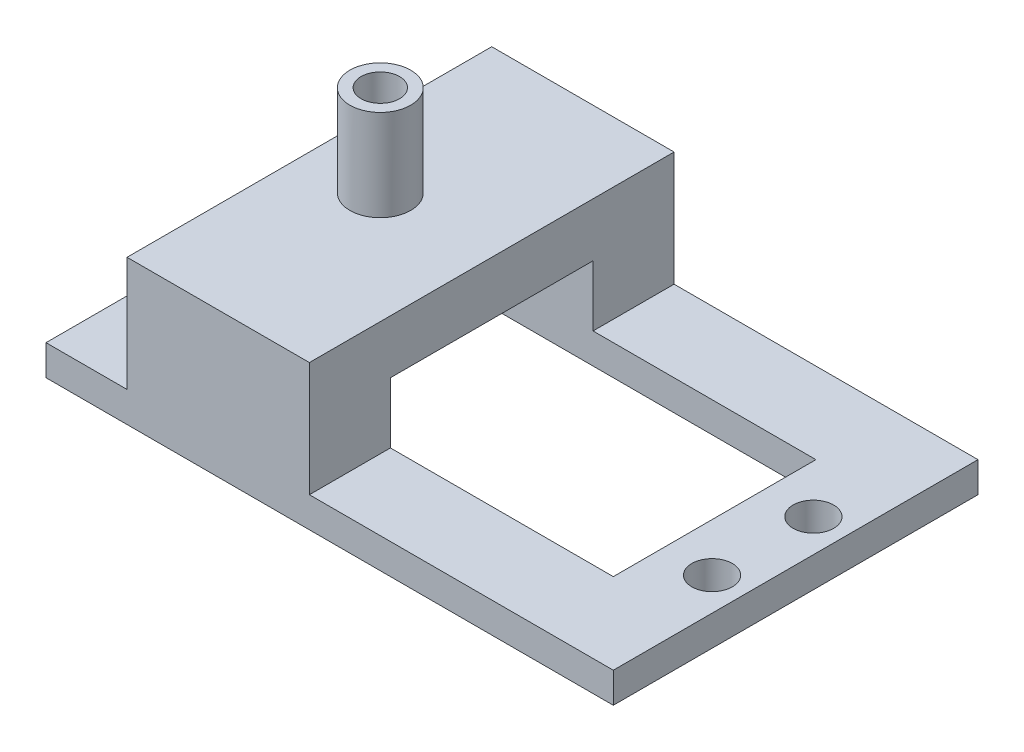
SolidWorks part; units mm, degrees
ref_plane "Front Plane" through (0, 0, 0) normal (0, 0, 1) x (1, 0, 0)
ref_plane "Top Plane" through (0, 0, 0) normal (0, 1, 0) x (1, 0, 0)
ref_plane "Right Plane" through (0, 0, 0) normal (1, 0, 0) x (0, 0, -1)
sketch "Sketch1" plane through (0, 0, 0) normal (0, 1, 0) x (1, 0, 0)
  line L1 (-29.0978, 4.5617) -> (-21.0978, 4.5617)
  line L2 (-29.0978, 4.5617) -> (-29.0978, -15.4383)
  line L3 (-29.0978, -15.4383) -> (-21.0978, -15.4383)
  line L4 (-21.0978, 4.5617) -> (-21.0978, -15.4383)
  line L5 (18.9022, 4.5617) -> (26.9022, 4.5617)
  line L6 (18.9022, 4.5617) -> (18.9022, -15.4383)
  line L7 (18.9022, -15.4383) -> (26.9022, -15.4383)
  line L8 (26.9022, 4.5617) -> (26.9022, -15.4383)
  line L9 (-29.0978, 4.5617) -> (26.9022, 4.5617)
  line L10 (-29.0978, 4.5617) -> (-29.0978, 12.5617)
  line L11 (-29.0978, 12.5617) -> (26.9022, 12.5617)
  line L12 (26.9022, 4.5617) -> (26.9022, 12.5617)
  line L13 (-29.0978, -15.4383) -> (26.9022, -15.4383)
  line L14 (-29.0978, -15.4383) -> (-29.0978, -23.4383)
  line L15 (-29.0978, -23.4383) -> (26.9022, -23.4383)
  line L16 (26.9022, -15.4383) -> (26.9022, -23.4383)
  dimension "D1" = 40
  dimension "D2" = 8
  dimension "D3" = 8
  dimension "D4" = 20
  dimension "D5" = 8
  dimension "D6" = 8
extrude "Boss-Extrude1" add sketch "Sketch1" against normal blind 3 contours L5 L12 L11 L10 L1 L9 | L4 L1 L2 L3 | L8 L5 L6 L7 | L14 L13 L16 L15
sketch "Sketch2" plane through (0, 0, 0) normal (0, 1, 0) x (1, 0, 0)
  line L0 (-29.0978, 12.5617) -> (26.9022, 12.5617) construction
  line L1 (-21.0978, 4.5617) -> (-3.0978, 4.5617)
  line L2 (-21.0978, 4.5617) -> (-21.0978, 12.5617)
  line L3 (-21.0978, 12.5617) -> (-3.0978, 12.5617)
  line L4 (-3.0978, 4.5617) -> (-3.0978, 12.5617)
  line L5 (-29.0978, -23.4383) -> (26.9022, -23.4383) construction
  line L6 (-21.0978, -15.4383) -> (-3.0978, -15.4383)
  line L7 (-21.0978, -15.4383) -> (-21.0978, -23.4383)
  line L8 (-21.0978, -23.4383) -> (-3.0978, -23.4383)
  line L9 (-3.0978, -15.4383) -> (-3.0978, -23.4383)
  dimension "D1" = 18
  dimension "D2" = 18
extrude "Boss-Extrude2" add sketch "Sketch2" along normal blind 6
sketch "Sketch3" plane through (0, 6, 0) normal (0, 1, 0) x (1, 0, 0)
  line L1 (-21.0978, -23.4383) -> (-3.0978, -23.4383)
  line L2 (-21.0978, -23.4383) -> (-21.0978, 12.5617)
  line L3 (-21.0978, 12.5617) -> (-3.0978, 12.5617)
  line L4 (-3.0978, -23.4383) -> (-3.0978, 12.5617)
extrude "Boss-Extrude3" add sketch "Sketch3" along normal blind 5.3
sketch "Sketch5" plane through (0, 6, 0) normal (0, 1, 0) x (1, 0, 0)
  line L0 (18.9022, 4.5617) -> (18.9022, -15.4383) construction
  circle A0 centre (-14.0978, -5.4383) radius 1.9
  dimension "D1" = 33
extrude "Cut-Extrude1" cut sketch "Sketch5" along normal blind 5.3
sketch "Sketch6" plane through (0, 11.3, 0) normal (0, 1, 0) x (1, 0, 0)
  circle A0 centre (-14.0978, -5.4383) radius 1.9
  circle A1 centre (-14.0978, -5.4383) radius 3
extrude "Boss-Extrude5" add sketch "Sketch6" along normal blind 9
sketch "Sketch7" plane through (0, 6, 0) normal (0, -1, 0) x (1, 0, 0)
  line L1 (-12.2506, 1.9576) -> (-10.1599, 5.2977)
  line L2 (-10.1599, 5.2977) -> (-12.0071, 8.7784)
  line L3 (-12.0071, 8.7784) -> (-15.945, 8.919)
  line L4 (-15.945, 8.919) -> (-18.0358, 5.5789)
  line L5 (-18.0358, 5.5789) -> (-16.1886, 2.0982)
  line L6 (-16.1886, 2.0982) -> (-12.2506, 1.9576)
  circle A0 centre (-14.0978, 5.4383) radius 3.4125 construction
extrude "Cut-Extrude2" cut sketch "Sketch7" against normal blind 3
sketch "Sketch8" plane through (0, 0, 0) normal (0, 1, 0) x (1, 0, 0)
  line L3 (18.9022, 4.5617) -> (18.9022, -15.4383) construction
  line L4 (-3.0978, 12.5617) -> (26.9022, 12.5617) construction
  circle A0 centre (23.6522, -0.4383) radius 2
  circle A1 centre (23.6522, -10.4383) radius 2
  circle A2 centre (-25.8478, -0.4383) radius 2
  circle A3 centre (-25.8478, -10.4383) radius 2
  dimension "D1" = 10
  dimension "D2" = 10
  dimension "D3" = 49.5
  dimension "D4" = 4.75
  dimension "D5" = 13
extrude "Cut-Extrude3" cut sketch "Sketch8" against normal blind 3
